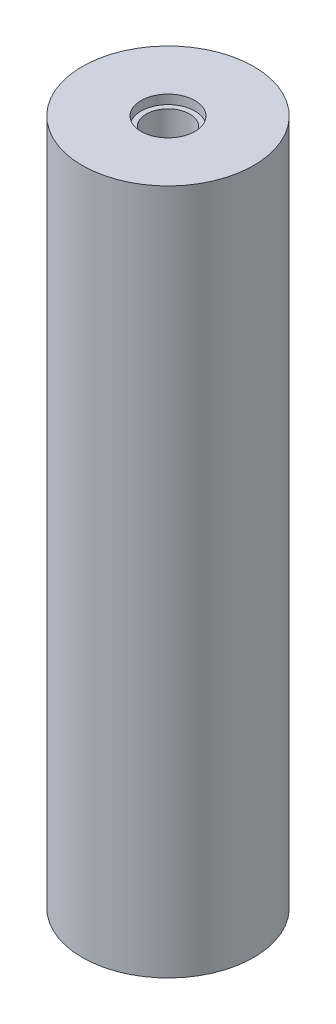
SolidWorks part; units mm, degrees
ref_plane "Front Plane" through (0, 0, 0) normal (0, 0, 1) x (1, 0, 0)
ref_plane "Top Plane" through (0, 0, 0) normal (0, 1, 0) x (1, 0, 0)
ref_plane "Right Plane" through (0, 0, 0) normal (1, 0, 0) x (0, 0, -1)
sketch "Sketch1" plane through (0, 0, 0) normal (0, 1, 0) x (1, 0, 0)
  circle A0 centre (0, 0) radius 7.5
  dimension "D1" = 15
extrude "Boss-Extrude1" add sketch "Sketch1" along normal blind 60
sketch "Sketch2" plane through (0, 60, 0) normal (0, 1, 0) x (1, 0, 0)
  circle A0 centre (0, 0) radius 1.9
  dimension "D1" = 3.8
extrude "Cut-Extrude1" cut sketch "Sketch2" against normal blind 5.2
sketch "Sketch3" plane through (0, 0, 0) normal (0, -1, 0) x (1, 0, 0)
  circle A0 centre (0, 0) radius 1.9
  dimension "D1" = 3.8
extrude "Cut-Extrude2" cut sketch "Sketch3" against normal blind 5.2
sketch "Sketch4" plane through (0, 60, 0) normal (0, 1, 0) x (1, 0, 0)
  circle A0 centre (0, 0) radius 2.35
  dimension "D1" = 4.7
extrude "Cut-Extrude3" cut sketch "Sketch4" against normal blind 0.8
sketch "Sketch5" plane through (0, 0, 0) normal (0, -1, 0) x (1, 0, 0)
  circle A0 centre (0, 0) radius 2.35
  dimension "D1" = 4.7
extrude "Cut-Extrude4" cut sketch "Sketch5" against normal blind 0.8
